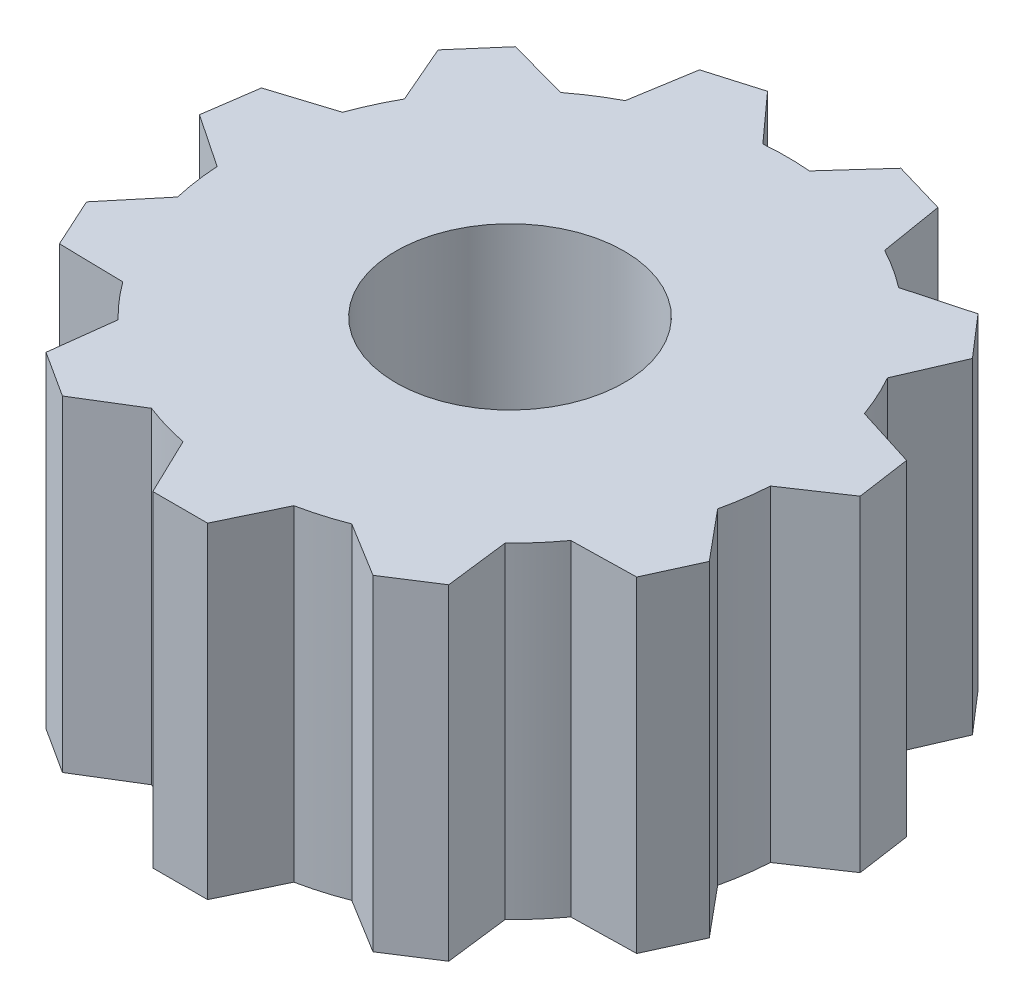
SolidWorks part; units mm, degrees
ref_plane "Front Plane" through (0, 0, 0) normal (0, 0, 1) x (1, 0, 0)
ref_plane "Top Plane" through (0, 0, 0) normal (0, 1, 0) x (1, 0, 0)
ref_plane "Right Plane" through (0, 0, 0) normal (1, 0, 0) x (0, 0, -1)
sketch "Sketch1" plane through (0, 0, 0) normal (0, 1, 0) x (1, 0, 0)
  circle A0 centre (0, 0) radius 3.5
extrude "Boss-Extrude1" add sketch "Sketch1" along normal blind 5
sketch "Sketch2" plane through (0, 5, 0) normal (0, 1, 0) x (1, 0, 0)
  circle A0 centre (0, 0) radius 3.5
ref_plane "Plane2" through (0, 5, 0) normal (0, -1, 0) x (-1, 0, 0)
sketch "Sketch12" plane through (0, 5, 0) normal (0, -1, 0) x (-1, 0, 0)
  circle A0 centre (0, 0) radius 3.5 construction
  circle A2 centre (0, 0) radius 12.5 construction
  circle A3 centre (0, 0) radius 8.5
  circle A4 centre (0, 0) radius 10.5 construction
  circle A5 centre (0, 0) radius 3.5
  dimension "D1" = 17
  dimension "D2" = 21
  dimension "D3" = 25
extrude "Boss-Extrude6" add sketch "Sketch12" along normal blind 5 separate body
sketch "Sketch13" plane through (0, 0, 0) normal (0, -1, 0) x (1, 0, 0)
  line L0 (0, 12.15) -> (0, -12.15) construction
  line L1 (-12.15, 0) -> (12.15, 0) construction
  line L2 (0.84, 10.1152) -> (1.7, 8.3283)
  line L3 (-0.84, 10.1152) -> (-1.7, 8.3283)
  line L4 (-0.84, 10.1152) -> (0.84, 10.1152)
  line L5 (-1.7, 8.3283) -> (3.0394, 8.1572) construction
  circle A0 centre (0, 0) radius 10.15 construction
  circle A1 centre (0, 0) radius 12.15 construction
  circle A3 centre (0, 0) radius 8.5 construction
  circle A4 centre (0, 0) radius 8.5
  circle A5 centre (0, 0) radius 8.5
  circle A6 centre (0, 0) radius 8.5
  point P11 (0, 0)
  circle M1 centre (0, 0) radius 8.5
  dimension "D1" = 20.3
  dimension "D2" = 24.3
  dimension "D3" = 17
  dimension "D4" = 1.7
  dimension "D5" = 1.7
  dimension "D6" = 1.68
  dimension "D7" = 66.367
  dimension "D8" = 0
extrude "Boss-Extrude9" add sketch "Sketch13" against normal blind 5 separate body contours L4 L3 L2 M1
pattern_circular "CirPattern2" count 11 over 360 about axis through (0, 0, 0) along (0, 1, 0) of bodies 130
sketch "Sketch14" plane through (0, 5, 0) normal (0, 1, 0) x (1, 0, 0)
  circle A0 centre (0, 0) radius 3.5 construction
  circle A1 centre (0, 0) radius 3.5
extrude "Cut-Extrude1" cut sketch "Sketch14" against normal blind 10
sketch "Sketch17" plane through (0, 0, 0) normal (0, -1, 0) x (1, 0, 0)
  line L0 (7.0945, -7.2589) -> (8.1946, -5.9892) construction
  line L1 (8.1946, -5.9892) -> (7.4073, -4.1691) construction
  line L2 (5.1808, -6.7386) -> (7.0945, -7.2589) construction
  line L3 (2.0438, -9.9421) -> (3.6558, -9.4688) construction
  line L4 (3.6558, -9.4688) -> (3.9775, -7.512) construction
  line L5 (0.7152, -8.4699) -> (2.0438, -9.9421) construction
  line L6 (-3.6558, -9.4688) -> (-2.0438, -9.9421) construction
  line L7 (-2.0438, -9.9421) -> (-0.7152, -8.4699) construction
  line L8 (-3.9775, -7.512) -> (-3.6558, -9.4688) construction
  line L9 (-8.1946, -5.9892) -> (-7.0945, -7.2589) construction
  line L10 (-7.0945, -7.2589) -> (-5.1808, -6.7386) construction
  line L11 (-7.4073, -4.1691) -> (-8.1946, -5.9892) construction
  line L12 (-10.1318, -0.6081) -> (-9.8927, -2.271) construction
  line L13 (-9.8927, -2.271) -> (-8.0016, -2.8679) construction
  line L14 (-8.4854, 0.4975) -> (-10.1318, -0.6081) construction
  line L15 (-4.762, 8.9636) -> (-6.1753, 8.0553) construction
  line L16 (-6.1753, 8.0553) -> (-5.9327, 6.0871) construction
  line L17 (-3.0725, 7.9253) -> (-4.762, 8.9636) construction
  line L18 (-8.8521, 4.9661) -> (-9.55, 3.4379) construction
  line L19 (-9.55, 3.4379) -> (-8.2819, 1.9133) construction
  line L20 (-6.8695, 5.0061) -> (-8.8521, 4.9661) construction
  line L21 (9.8927, -2.271) -> (10.1318, -0.6081) construction
  line L22 (10.1318, -0.6081) -> (8.4854, 0.4975) construction
  line L23 (8.0016, -2.8679) -> (9.8927, -2.271) construction
  line L24 (9.55, 3.4379) -> (8.8521, 4.9661) construction
  line L25 (8.8521, 4.9661) -> (6.8695, 5.0061) construction
  line L26 (8.2819, 1.9133) -> (9.55, 3.4379) construction
  line L27 (0.84, 10.1152) -> (-0.84, 10.1152) construction
  line L28 (-0.84, 10.1152) -> (-1.7, 8.3283) construction
  line L29 (1.7, 8.3283) -> (0.84, 10.1152) construction
  line L30 (7.0945, -7.2589) -> (8.1946, -5.9892)
  line L31 (8.1946, -5.9892) -> (7.4073, -4.1691)
  line L32 (5.1808, -6.7386) -> (7.0945, -7.2589)
  line L33 (2.0438, -9.9421) -> (3.6558, -9.4688)
  line L34 (3.6558, -9.4688) -> (3.9775, -7.512)
  line L35 (0.7152, -8.4699) -> (2.0438, -9.9421)
  line L36 (-3.6558, -9.4688) -> (-2.0438, -9.9421)
  line L37 (-2.0438, -9.9421) -> (-0.7152, -8.4699)
  line L38 (-3.9775, -7.512) -> (-3.6558, -9.4688)
  line L39 (-8.1946, -5.9892) -> (-7.0945, -7.2589)
  line L40 (-7.0945, -7.2589) -> (-5.1808, -6.7386)
  line L41 (-7.4073, -4.1691) -> (-8.1946, -5.9892)
  line L42 (-10.1318, -0.6081) -> (-9.8927, -2.271)
  line L43 (-9.8927, -2.271) -> (-8.0016, -2.8679)
  line L44 (-8.4854, 0.4975) -> (-10.1318, -0.6081)
  line L45 (-4.762, 8.9636) -> (-6.1753, 8.0553)
  line L46 (-6.1753, 8.0553) -> (-5.9327, 6.0871)
  line L47 (-3.0725, 7.9253) -> (-4.762, 8.9636)
  line L48 (-8.8521, 4.9661) -> (-9.55, 3.4379)
  line L49 (-9.55, 3.4379) -> (-8.2819, 1.9133)
  line L50 (-6.8695, 5.0061) -> (-8.8521, 4.9661)
  line L51 (9.8927, -2.271) -> (10.1318, -0.6081)
  line L52 (10.1318, -0.6081) -> (8.4854, 0.4975)
  line L53 (8.0016, -2.8679) -> (9.8927, -2.271)
  line L54 (9.55, 3.4379) -> (8.8521, 4.9661)
  line L55 (8.8521, 4.9661) -> (6.8695, 5.0061)
  line L56 (8.2819, 1.9133) -> (9.55, 3.4379)
  line L57 (0.84, 10.1152) -> (-0.84, 10.1152)
  line L58 (-0.84, 10.1152) -> (-1.7, 8.3283)
  line L59 (1.7, 8.3283) -> (0.84, 10.1152)
  arc A0 (5.1808, -6.7386) -> (7.4073, -4.1691) centre (0, 0) ccw construction
  arc A1 (0.7152, -8.4699) -> (3.9775, -7.512) centre (0, 0) ccw construction
  arc A2 (-3.9775, -7.512) -> (-0.7152, -8.4699) centre (0, 0) ccw construction
  arc A4 (-7.4073, -4.1691) -> (-5.1808, -6.7386) centre (0, 0) ccw construction
  arc A5 (-8.4854, 0.4975) -> (-8.0016, -2.8679) centre (0, 0) ccw construction
  arc A6 (-3.0725, 7.9253) -> (-5.9327, 6.0871) centre (0, 0) ccw construction
  arc A7 (-6.8695, 5.0061) -> (-8.2819, 1.9133) centre (0, 0) ccw construction
  arc A8 (8.0016, -2.8679) -> (8.4854, 0.4975) centre (0, 0) ccw construction
  arc A9 (8.2819, 1.9133) -> (6.8695, 5.0061) centre (0, 0) ccw construction
  arc A10 (1.7, 8.3283) -> (-1.7, 8.3283) centre (0, 0) ccw construction
  circle A11 centre (0, 0) radius 8.5 construction
  arc A12 (5.1808, -6.7386) -> (7.4073, -4.1691) centre (0, 0) ccw
  arc A13 (0.7152, -8.4699) -> (3.9775, -7.512) centre (0, 0) ccw
  arc A14 (-3.9775, -7.512) -> (-0.7152, -8.4699) centre (0, 0) ccw
  arc A15 (-7.4073, -4.1691) -> (-5.1808, -6.7386) centre (0, 0) ccw
  arc A16 (-8.4854, 0.4975) -> (-8.0016, -2.8679) centre (0, 0) ccw
  arc A17 (-3.0725, 7.9253) -> (-5.9327, 6.0871) centre (0, 0) ccw
  arc A18 (-6.8695, 5.0061) -> (-8.2819, 1.9133) centre (0, 0) ccw
  arc A19 (8.0016, -2.8679) -> (8.4854, 0.4975) centre (0, 0) ccw
  arc A20 (8.2819, 1.9133) -> (6.8695, 5.0061) centre (0, 0) ccw
  arc A21 (1.7, 8.3283) -> (-1.7, 8.3283) centre (0, 0) ccw
  circle A22 centre (0, 0) radius 8.5
  circle M1 centre (0, 0) radius 8.5
  circle M2 centre (0, 0) radius 3.5
  dimension "D1" = 6.1449
other "AlignGroup1"
other "AlignGroup2"
extrude "Boss-Extrude10" add sketch "Sketch17" along normal blind 5 contours M1 M2 | L59 L57 L58 M1 | L47 L45 L46 M1 | L50 L48 L49 M1 | L44 L42 L43 M1 | L41 L39 L40 M1 | L38 L36 L37 M1 | L35 L33 L34 M1 | L32 L30 L31 M1 | L53 L51 L52 M1 | L56 L54 L55 M1
sketch "Sketch18" plane through (0, 0, 0) normal (0, -1, 0) x (1, 0, 0)
  line L3 (6.1753, 8.0553) -> (4.762, 8.9636)
  line L4 (4.762, 8.9636) -> (3.0725, 7.9253)
  line L5 (5.9327, 6.0871) -> (6.1753, 8.0553)
  line L6 (6.1753, 8.0553) -> (4.762, 8.9636)
  line L7 (4.762, 8.9636) -> (3.0725, 7.9253)
  line L8 (5.9327, 6.0871) -> (6.1753, 8.0553)
  arc A1 (5.9327, 6.0871) -> (3.0725, 7.9253) centre (0, 0) ccw
  arc A2 (5.9327, 6.0871) -> (3.0725, 7.9253) centre (0, 0) ccw
  dimension "D1" = 0
extrude "Boss-Extrude11" add sketch "Sketch18" along normal blind 5
